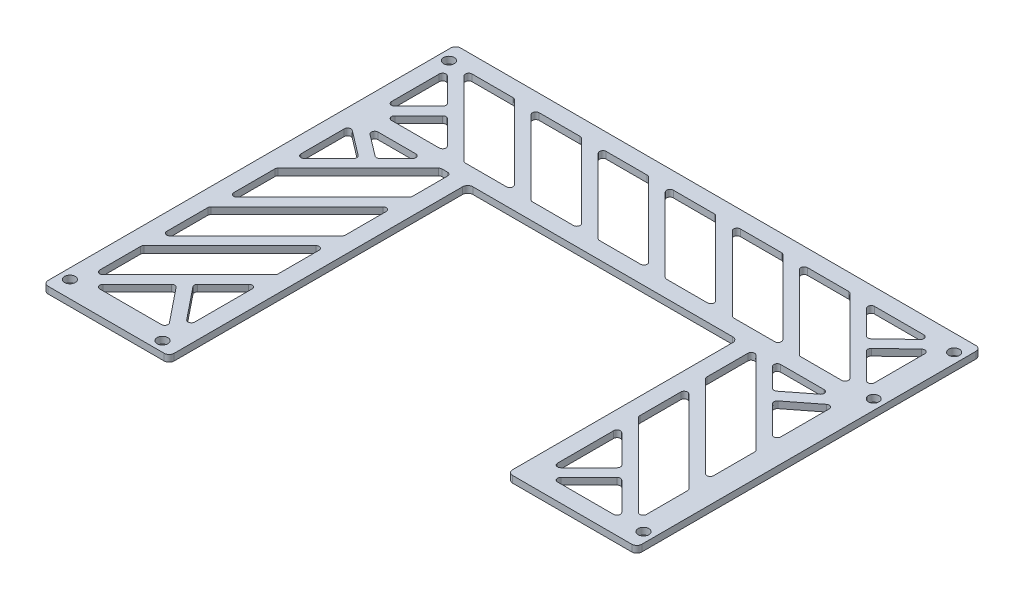
SolidWorks part; units mm, degrees
material "Thornel Mat VMA"
ref_plane "前视基准面" through (0, 0, 0) normal (0, 0, 1) x (1, 0, 0)
ref_plane "上视基准面" through (0, 0, 0) normal (0, 1, 0) x (1, 0, 0)
ref_plane "右视基准面" through (0, 0, 0) normal (1, 0, 0) x (0, 0, -1)
other "Configuration Table"
sketch "草图1" plane through (0, 0, 0) normal (0, 1, 0) x (1, 0, 0)
  line L0 (0, 0) -> (0, -89)
  line L1 (0, -89) -> (-37.6, -89)
  line L2 (-37.6, -89) -> (-37.6, 34)
  line L3 (-37.6, 34) -> (119, 34)
  line L4 (119, 34) -> (119, -68.6)
  line L5 (119, -68.6) -> (80.5, -68.6)
  line L6 (80.5, -68.6) -> (80.5, 0)
  line L7 (80.5, 0) -> (0, 0)
  dimension "D1" = 37.6
  dimension "D2" = 89
  dimension "D3" = 156.6
  dimension "D4" = 34
  dimension "D5" = 38.5
  dimension "D6" = 68.6
extrude "凸台-拉伸1" add sketch "草图1" along normal blind 2
sketch "草图2" plane through (0, 2, 0) normal (0, 1, 0) x (1, 0, 0)
  line L0 (-37.6, 34) -> (-37.6, -89) construction
  line L1 (-37.6, -89) -> (0, -89) construction
  line L2 (0, -89) -> (0, 0) construction
  line L4 (119, -68.6) -> (119, 34) construction
  line L5 (80.5, -68.6) -> (119, -68.6) construction
  line L6 (0, 0) -> (80.5, 0) construction
  line L7 (119, 34) -> (-37.6, 34) construction
  circle A0 centre (-34.6, -84) radius 1.6
  circle A1 centre (-5, -86) radius 1.6
  circle A2 centre (-34.6, 29) radius 1.6
  circle A4 centre (116, 5) radius 1.6
  circle A5 centre (116, -63.6) radius 1.6
  dimension "D1" = 3.2
  dimension "D2" = 3
  dimension "D3" = 5
  dimension "D4" = 5
  dimension "D5" = 3
  dimension "D6" = 5
  dimension "D7" = 3
  dimension "D8" = 5
  dimension "D9" = 5
extrude "切除-拉伸1" cut sketch "草图2" against normal blind 2
sketch "草图3" plane through (0, 2, 0) normal (0, 1, 0) x (1, 0, 0)
  line L0 (-5, 0) -> (-5, -82)
  line L1 (-5, -82) -> (-32.6, -82)
  line L2 (-32.6, -82) -> (-32.6, 0)
  line L3 (-32.6, 29) -> (112, 29)
  line L4 (112, 29) -> (112, 5)
  line L5 (112, -63.6) -> (85.5, -63.6)
  line L6 (85.5, -63.6) -> (85.5, 0)
  line L7 (85.5, 5) -> (-5, 5)
  line L8 (0, -89) -> (0, 0) construction
  line L9 (-37.6, 34) -> (-37.6, -89) construction
  line L10 (119, 34) -> (-37.6, 34) construction
  line L11 (0, 0) -> (80.5, 0) construction
  line L12 (80.5, 0) -> (80.5, -68.6) construction
  line L13 (80.5, -68.6) -> (119, -68.6) construction
  line L14 (-5, 0) -> (-32.6, 0)
  line L15 (-5, 5) -> (-32.6, 5)
  line L16 (85.5, 0) -> (112, 0)
  line L17 (85.5, 5) -> (112, 5)
  line L18 (112, 0) -> (112, -63.6)
  line L19 (-32.6, 5) -> (-32.6, 29)
  circle A2 centre (-5, -86) radius 4 construction
  circle A3 centre (116, -63.6) radius 4 construction
  dimension "D1" = 8
  dimension "D2" = 5
  dimension "D3" = 5
  dimension "D4" = 5
  dimension "D5" = 5
  dimension "D6" = 5
  dimension "D7" = 5
extrude "切除-拉伸2" cut sketch "草图3" against normal blind 10
sketch "草图7" plane through (0, 2, 0) normal (0, 1, 0) x (1, 0, 0)
  line L0 (-34.6, -84) -> (0, -49.4)
  line L1 (0, -89) -> (0, 0) construction
  line L2 (-32.6, -82) -> (-5, -82) construction
  line L3 (-34.6, -64) -> (0, -29.4)
  line L4 (-34.6, -44) -> (0, -9.4)
  line L5 (-34.6, -24) -> (-5.6, 5)
  line L6 (-32.6, 5) -> (112, 5) construction
  line L7 (-32.6, 5) -> (112, 5) construction
  line L8 (117, -68.6) -> (80.5, -32.1)
  line L12 (80.5, -68.6) -> (119, -68.6) construction
  line L13 (85.5, -63.6) -> (112, -63.6) construction
  line L14 (117, -48.6) -> (80.5, -12.1)
  line L15 (-37.6, 34) -> (-3.6, 0)
  line L16 (-5, 0) -> (-32.6, 0) construction
  line L17 (-32.6, 29) -> (-32.6, 5) construction
  line L18 (-17.6, 34) -> (16.4, 0)
  line L19 (2.4, 34) -> (36.4, 0)
  line L20 (22.4, 34) -> (56.4, 0)
  line L21 (42.4, 34) -> (76.4, 0)
  line L22 (62.4, 34) -> (96.4, 0)
  line L23 (82.4, 34) -> (116.4, 0)
  line L24 (-32.6, 5) -> (-20.6, 17)
  line L25 (112, 29) -> (99.4, 17)
  line L26 (-5, -82) -> (-17.3, -66.7)
  line L27 (-32.6, 0) -> (-20.1, -9.5)
  line L28 (117, -28.6) -> (80.5, 7.9)
  line L29 (80.5, 0) -> (80.5, -68.6) construction
  line L30 (85.5, -63.6) -> (98.75, -50.35)
  line L31 (112, 0) -> (98.75, -10.35)
  dimension "D1" = 45
  dimension "D3" = 20
  dimension "D4" = 45
  dimension "D6" = 20
  dimension "D7" = 45
  dimension "D9" = 20
  dimension "D2" = 4
  dimension "D8" = 7
  dimension "D5" = 3
extrude "拉伸-薄壁6" add sketch "草图7" against normal blind 2 thin thin type mid plane wall 3.5
sketch "草图8" plane through (0, 2, 0) normal (0, 1, 0) x (1, 0, 0)
  line L0 (114.5251, -68.6) -> (115.7626, -69.8374)
  line L1 (115.7626, -69.8374) -> (117, -68.6)
  line L2 (117, -68.6) -> (114.5251, -68.6)
  line L4 (0, -89) -> (80.5, -89)
  line L5 (0, -89) -> (0, 0)
  line L6 (0, 0) -> (80.5, 0)
  line L7 (80.5, -89) -> (80.5, 0)
  line L8 (119, 34) -> (-37.6, 34)
  line L9 (119, 34) -> (119, 36)
  line L10 (119, 36) -> (-45.6, 36)
  line L11 (-45.6, 34) -> (-45.6, 36)
  line L12 (-37.6, -89) -> (-45.6, -89)
  line L13 (-37.6, -89) -> (-37.6, 34)
  line L15 (-45.6, -89) -> (-45.6, 34)
  line L27 (-33.4686, -85.1314) -> (-35.7314, -82.8686) construction
  line L33 (80.9251, 5) -> (85.8749, 5)
  line L34 (85.8749, 5) -> (81.7374, 9.1374)
  line L35 (81.7374, 9.1374) -> (79.2626, 6.6626)
  line L36 (79.2626, 6.6626) -> (80.9251, 5)
  line L37 (85.9251, 0) -> (85.5, 0.4251)
  line L38 (85.5, 0.4251) -> (85.5, 0)
  line L39 (93.9251, 0) -> (95.1626, -1.2374)
  line L40 (95.1626, -1.2374) -> (96.4, 0)
  line L41 (96.4, 0) -> (93.9251, 0)
  line L42 (85.5, 0) -> (85.9251, 0)
  line L43 (112, -26.0749) -> (85.9251, 0) construction
  line L44 (-6.8374, 6.2374) -> (-5.6, 5)
  line L45 (-5.6, 5) -> (-6.1251, 5)
  line L46 (-6.1251, 5) -> (-7.1, 5.9749)
  line L47 (-30.1251, 29) -> (-7.1, 5.9749) construction
  line L48 (-5, -1.0749) -> (-6.0749, 0)
  line L49 (-6.0749, 0) -> (-5, 0)
  line L50 (-5, 0) -> (-5, -1.0749)
  line L51 (-6.8374, 6.2374) -> (-7.1, 5.9749)
  circle A0 centre (116, -63.6) radius 1.6
  circle A1 centre (-34.6, 29) radius 1.6
  circle A2 centre (-34.6, -84) radius 1.6
  dimension "D1" = 8
  dimension "D2" = 2
extrude "切除-拉伸3" cut sketch "草图8" against normal blind 2
fillet "圆角2" radius 1.5 8 edges at (-37.6, 1, 89) (-37.6, 1, -34) (119, 1, -34) (119, 1, 68.6) (80.5, 1, 68.6) (80.5, 1, 0) (0, 1, 0) (0, 1, 89)
fillet "圆角3" radius 1 83 edges at (98.75, 1, 52.8249) (85.5, 1, 61.1251) (112, 1, 21.1251) (85.5, 1, 14.6251) (-30.1251, 1, 82) (-32.6, 1, 44.4749) (-32.6, 1, 24.4749) (-32.6, 1, 2.198) (-32.6, 1, 64.4749) (-8.1251, 1, 0) (-5, 1, 16.8749) (-5, 1, 36.8749) (-32.6, 1, -26.5251) (-11.0749, 1, -5) (-30.1251, 1, -5) (8.9251, 1, -5) (112, 1, 41.1251) (112, 1, 61.1251) (85.5, 1, -0.4251) (85.5, 1, 34.6251) (108.9251, 1, -5) (-6.1251, 1, -5) (68.9251, 1, -5) (88.9251, 1, -5) (-5, 1, 0) (28.9251, 1, -5) (48.9251, 1, -5) (90.8749, 1, 0) (-5, 1, 56.8749) (-5, 1, 79.207) (-23.0749, 1, -17) (-32.6, 1, -7.4749) (-14.9523, 1, 66.8272) (-32.6, 1, 79.5251) (-5, 1, 51.9251) (-7.2454, 1, 82) (-17.4418, 1, 69.3167) (-32.6, 1, 39.5251) (-5, 1, 11.9251) (-32.6, 1, 59.5251) (-5, 1, 31.9251) (-32.6, 1, 19.5251) (-22.7551, 1, 9.6802) (-29.7078, 1, 0) (-20.2573, 1, 7.1824) (-13.0749, 1, 0) (101.3862, 1, 10.5114) (112, 1, 2.2206) (98.8928, 1, 8.0179) (112, 1, 26.0749) (109.5251, 1, 63.6) (85.5, 1, 39.5749) (96.2751, 1, 50.35) (112, 1, -6.8749) (101.9054, 1, -16.9695) (89.8749, 1, -29) (-30.1251, 1, -29) (-20.6, 1, -14.5251) (33.8749, 1, -5) (9.8749, 1, -29) (13.8749, 1, -5) (-10.1251, 1, -29) (73.8749, 1, -5) (49.8749, 1, -29) (53.8749, 1, -5) (29.8749, 1, -29) (93.8749, 1, -5) (69.8749, 1, -29) (115.326, 1, -3.5489) (114.5489, 1, -4.326) (109.1572, 1, 0) (87.9749, 1, 63.6) (84.9251, 1, -29) (112, 1, 46.0749) (109.4625, 1, -29) (85.5, 1, 19.5749) (-15.0749, 1, -29) (44.9251, 1, -29) (64.9251, 1, -29) (4.9251, 1, -29) (24.9251, 1, -29) (99.4298, 1, -19.4451) (112, 1, -26.5833)
sketch "草图9" plane through (0, 2, 0) normal (0, 1, 0) x (1, 0, 0)
  line L0 (119, -67.1) -> (119, 32.5) construction
  line L1 (117.5, 34) -> (-36.1, 34) construction
  circle A0 centre (116, 29) radius 1.6
  circle A1 centre (116, 5) radius 1.6 construction
  dimension "D1" = 3
  dimension "D2" = 5
extrude "切除-拉伸4" cut sketch "草图9" against normal blind 2
